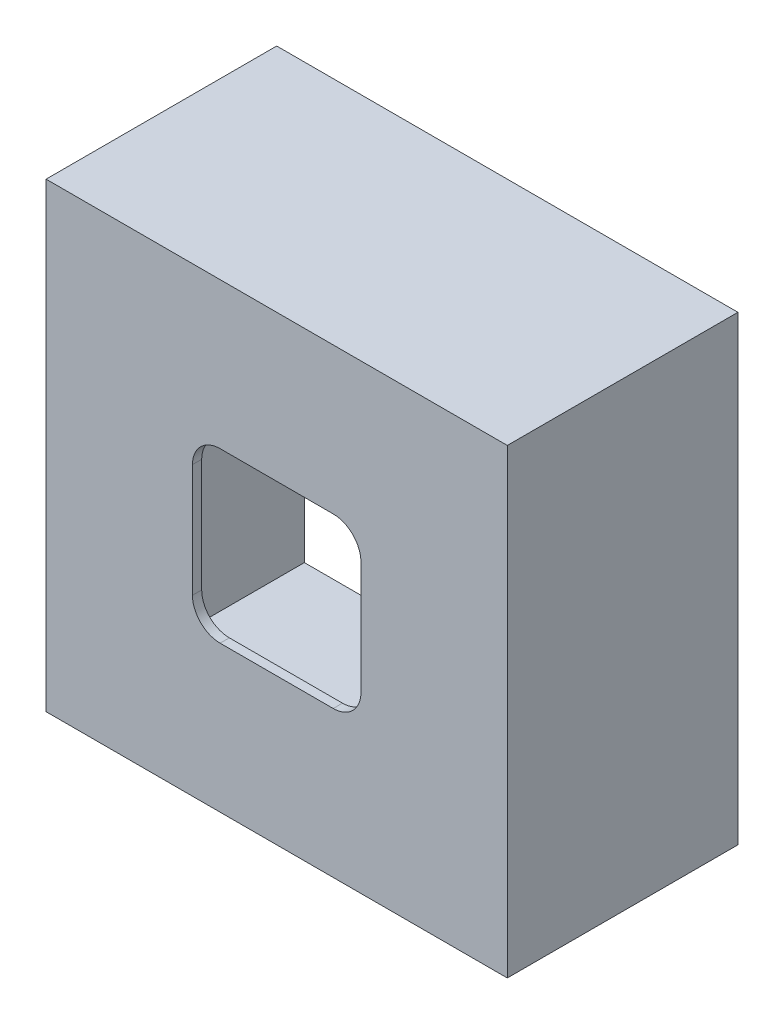
SolidWorks part; units mm, degrees
ref_plane "Front Plane" through (0, 0, 0) normal (0, 0, 1) x (1, 0, 0)
ref_plane "Top Plane" through (0, 0, 0) normal (0, 1, 0) x (1, 0, 0)
ref_plane "Right Plane" through (0, 0, 0) normal (1, 0, 0) x (0, 0, -1)
sketch "Sketch1" plane through (0, 0, 0) normal (0, 0, 1) x (1, 0, 0)
  line L4 (12.2635, 18.2635) -> (-12.2635, 18.2635)
  line L5 (18.2635, -12.2635) -> (18.2635, 12.2635)
  line L6 (-12.2635, -18.2635) -> (12.2635, -18.2635)
  line L7 (-18.2635, 12.2635) -> (-18.2635, -12.2635)
  line L8 (-48, 48) -> (-48, -48) construction
  line L9 (50, 50) -> (-50, 50)
  line L10 (50, 50) -> (50, -50)
  line L11 (50, -50) -> (-50, -50)
  line L12 (-50, 50) -> (-50, -50)
  line L13 (50, 50) -> (-50, -50) construction
  line L14 (50, -50) -> (-50, 50) construction
  line L15 (48, 48) -> (-48, 48) construction
  line L16 (-18.2635, 12.2635) -> (-18.2635, -12.2635) construction
  line L20 (12.2635, 18.2635) -> (-12.2635, 18.2635) construction
  line L21 (18.2635, -12.2635) -> (18.2635, 12.2635) construction
  line L22 (-12.2635, -18.2635) -> (12.2635, -18.2635) construction
  arc A4 (-12.2635, 18.2635) -> (-18.2635, 12.2635) centre (-12.2635, 12.2635) ccw
  arc A5 (18.2635, 12.2635) -> (12.2635, 18.2635) centre (12.2635, 12.2635) ccw
  arc A6 (12.2635, -18.2635) -> (18.2635, -12.2635) centre (12.2635, -12.2635) ccw
  arc A7 (-18.2635, -12.2635) -> (-12.2635, -18.2635) centre (-12.2635, -12.2635) ccw
  arc A10 (18.2635, 12.2635) -> (12.2635, 18.2635) centre (12.2635, 12.2635) ccw construction
  arc A11 (-12.2635, 18.2635) -> (-18.2635, 12.2635) centre (-12.2635, 12.2635) ccw construction
  arc A12 (12.2635, -18.2635) -> (18.2635, -12.2635) centre (12.2635, -12.2635) ccw construction
  arc A13 (-18.2635, -12.2635) -> (-12.2635, -18.2635) centre (-12.2635, -12.2635) ccw construction
  point P4 (0, 0)
  dimension "D1" = 2
  dimension "D2" = 2
extrude "Boss-Extrude1" add sketch "Sketch1" against normal up to surface (2 mm away)
sketch "Sketch2" plane through (0, 0, -2) normal (0, 0, -1) x (-1, 0, 0)
  line L5 (-50, 50) -> (50, 50)
  line L6 (-50, 50) -> (-50, -50)
  line L7 (-50, -50) -> (50, -50)
  line L8 (50, 50) -> (50, -50)
  line L9 (-44, 44) -> (44, 44)
  line L10 (-44, 44) -> (-44, -44)
  line L11 (-44, -44) -> (44, -44)
  line L12 (44, 44) -> (44, -44)
extrude "Boss-Extrude2" add sketch "Sketch2" along normal blind 48
